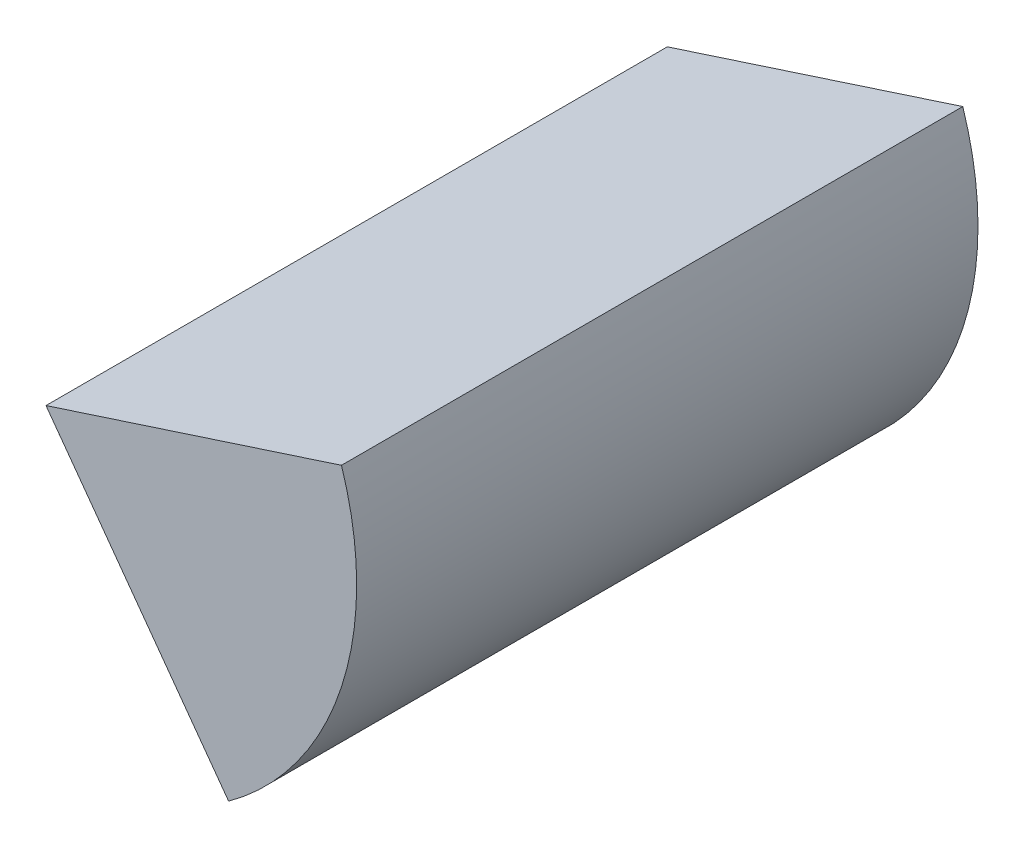
SolidWorks part; units mm, degrees
ref_plane "Alzado" through (0, 0, 0) normal (0, 0, 1) x (1, 0, 0)
ref_plane "Planta" through (0, 0, 0) normal (0, 1, 0) x (1, 0, 0)
ref_plane "Vista lateral" through (0, 0, 0) normal (1, 0, 0) x (0, 0, -1)
sketch "Croquis1" plane through (0, 0, 0) normal (0, 0, 1) x (1, 0, 0)
  line L1 (0, 0) -> (23.7764, 7.7254)
  line L2 (0, 0) -> (14.6946, -20.2254)
  arc A0 (14.6946, -20.2254) -> (23.7764, 7.7254) centre (0, 0) ccw
  dimension "D1" = 50
  dimension "D2" = 72
extrude "Saliente-Extruir1" add sketch "Croquis1" along normal blind 50
sketch "Croquis2" plane through (0, 0, 0) normal (0, 0, -1) x (-1, 0, 0)
  circle A0 centre (-15.1663, -4.6555) radius 5
  dimension "D1" = 10
extrude "Cortar-Extruir1" cut sketch "Croquis2" against normal blind 10
